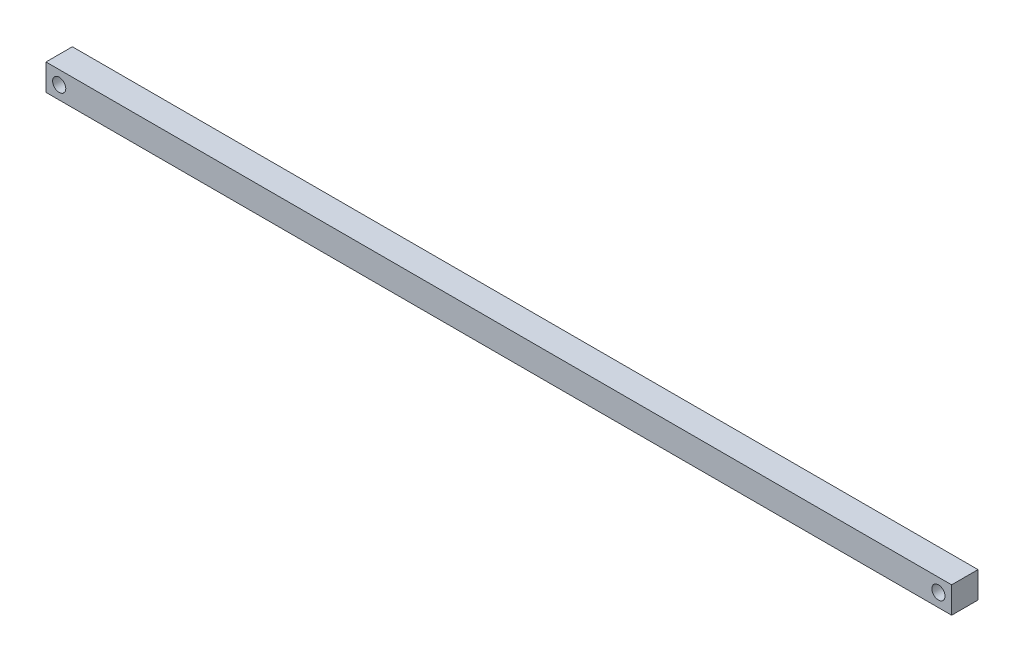
SolidWorks part; units mm, degrees
material "1060 Alloy for 162A"
ref_plane "Front Plane" through (0, 0, 0) normal (0, 0, 1) x (1, 0, 0)
ref_plane "Top Plane" through (0, 0, 0) normal (0, 1, 0) x (1, 0, 0)
ref_plane "Right Plane" through (0, 0, 0) normal (1, 0, 0) x (0, 0, -1)
sketch "Sketch1" plane through (0, 0, 0) normal (0, 0, 1) x (1, 0, 0)
  line L0 (500, 0) -> (-500, 0) construction
  line L1 (515, 15) -> (-515, 15)
  line L2 (515, 15) -> (515, -15)
  line L3 (515, -15) -> (-515, -15)
  line L4 (-515, 15) -> (-515, -15)
  line L5 (515, 15) -> (-515, -15) construction
  line L6 (515, -15) -> (-515, 15) construction
  circle A0 centre (-500, 0) radius 7.5
  circle A1 centre (500, 0) radius 7.5
  point P0 (0, 0)
  point P8 (0, 0)
  dimension "D2" = 15
  dimension "D1" = 30
  dimension "D3" = 1000
  dimension "D4" = 15
extrude "Boss-Extrude1" add sketch "Sketch1" along normal mid plane 30
equation "\"A\"= 200"
equation "\"hole_diameter\"=15"
equation "\"D2@Sketch1\"=\"hole_diameter\""
equation "\"D3@Sketch1\"=5*\"A\""
equation "\"D4@Sketch1\"=\"hole_diameter\""
